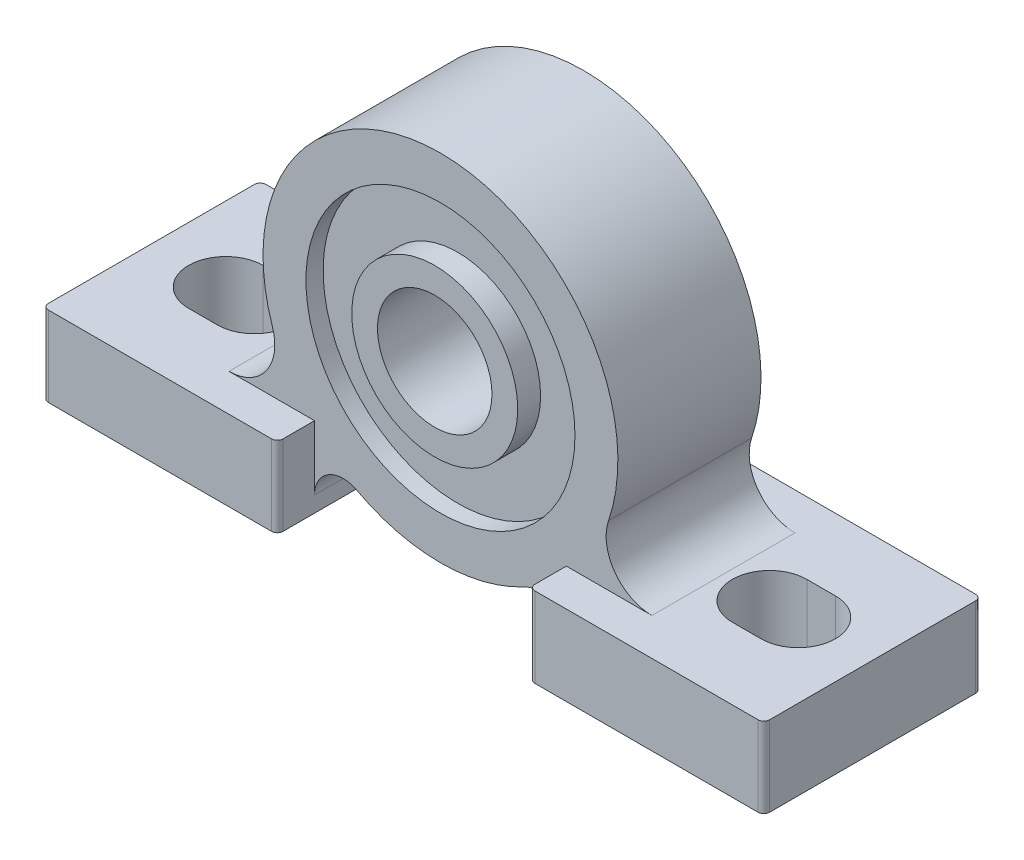
SolidWorks part; units mm, degrees
ref_plane "Спереди" through (0, 0, 0) normal (0, 0, 1) x (1, 0, 0)
ref_plane "Сверху" through (0, 0, 0) normal (0, 1, 0) x (1, 0, 0)
ref_plane "Справа" through (0, 0, 0) normal (1, 0, 0) x (0, 0, -1)
sketch "Эскиз8" plane through (0, 0, 0) normal (0, 0, 1) x (1, 0, 0)
  circle A0 centre (50, -1.5) radius 10
  circle A1 centre (50, -1.5) radius 14.5
  dimension "D1" = 20
  dimension "D2" = 29
extrude "Вытянуть1" add sketch "Эскиз8" along normal blind 31
ref_plane "Плоскость1" through (0, 0, 10) normal (0, 0, 1) x (1, 0, 0)
sketch "Эскиз10" plane through (0, 0, 10) normal (0, 0, 1) x (1, 0, 0)
  circle A0 centre (50, -1.5) radius 23.5
  circle A1 centre (50, -1.5) radius 14.5
  dimension "D1" = 29
  dimension "D2" = 47
extrude "Вытянуть2" add sketch "Эскиз10" along normal blind 17
sketch "Эскиз11" plane through (0, 0, 10) normal (0, 0, 1) x (1, 0, 0)
  circle A0 centre (50, -1.5) radius 23.5
  circle A1 centre (50, -1.5) radius 31
  dimension "D1" = 47
  dimension "D2" = 62
extrude "Вытянуть3" add sketch "Эскиз11" along normal blind 25 from offset 5 offset against normal yes
ref_plane "Плоскость2" through (0, -36, 0) normal (0, 1, 0) x (-1, 0, 0)
sketch "Эскиз13" plane through (0, -36, 0) normal (0, 1, 0) x (-1, 0, 0)
  line L1 (-95, 11) -> (-100, 11)
  line L2 (-28, 36.5) -> (13, 36.5)
  line L3 (-4.7401, 23.9948) -> (0, 24)
  line L4 (-95.2599, 23.9948) -> (-100, 24)
  line L5 (-5, 11) -> (0, 11)
  line L6 (13, -1.5) -> (13, 36.5)
  line L7 (-72, -1.5) -> (-113, -1.5)
  line L8 (-72, 36.5) -> (-113, 36.5)
  line L9 (-113, -1.5) -> (-113, 36.5)
  line L10 (-72, -1.5) -> (-72, 36.5)
  line L11 (-28, -1.5) -> (13, -1.5)
  line L12 (-28, -1.5) -> (-28, 36.5)
  arc A0 (-100, 24) -> (-100, 11) centre (-100, 17.5) ccw
  arc A1 (-95, 11) -> (-95.2599, 23.9948) centre (-95, 17.5) ccw
  arc A2 (-5, 11) -> (-4.7401, 23.9948) centre (-5, 17.5) cw
  arc A3 (0, 24) -> (0, 11) centre (0, 17.5) cw
  dimension "D1" = 6.5
  dimension "D2" = 6.5
  dimension "D3" = 6.5
  dimension "D4" = 6.5
  dimension "D5" = 41
  dimension "D6" = 38
  dimension "D7" = 44
  dimension "D8" = 41
  dimension "D9" = 38
  dimension "D10" = 18
  dimension "D11" = 13
  dimension "D12" = 41
  dimension "D13" = 38
  dimension "D14" = 38
  dimension "D15" = 41
  dimension "D16" = 13
  dimension "D17" = 113
  dimension "D18" = 4.7401
  dimension "D19" = 0.2599
  dimension "D20" = 23
  dimension "D21" = 0.2599
  dimension "D22" = 4.7401
  dimension "D23" = 17.5
  dimension "D24" = 17.5
  dimension "D25" = 23.9948
  dimension "D26" = 23.9948
  dimension "D27" = 36.5
  dimension "D28" = 36.5
extrude "Вытянуть4" add sketch "Эскиз13" along normal blind 14
ref_plane "Плоскость3" through (26.746, -22, 5) normal (0, 0, -1) x (-1, 0, 0)
fillet "Скругление1" radius 8 1 edges at (26.746, -22, 17.5)
fillet "Скругление2" radius 5 1 edges at (28, -23.3403, 17.5)
fillet "Скругление3" radius 5 1 edges at (72, -23.3403, 17.5)
fillet "Скругление4" radius 8 1 edges at (73.254, -22, 17.5)
fillet "Скругление5" radius 1 4 edges at (28, -29, 36.5) (28, -29, -1.5) (72, -29, 36.5) (72, -29, -1.5)
fillet "Скругление6" radius 1 4 edges at (-13, -29, -1.5) (-13, -29, 36.5) (113, -29, 36.5) (113, -29, -1.5)
